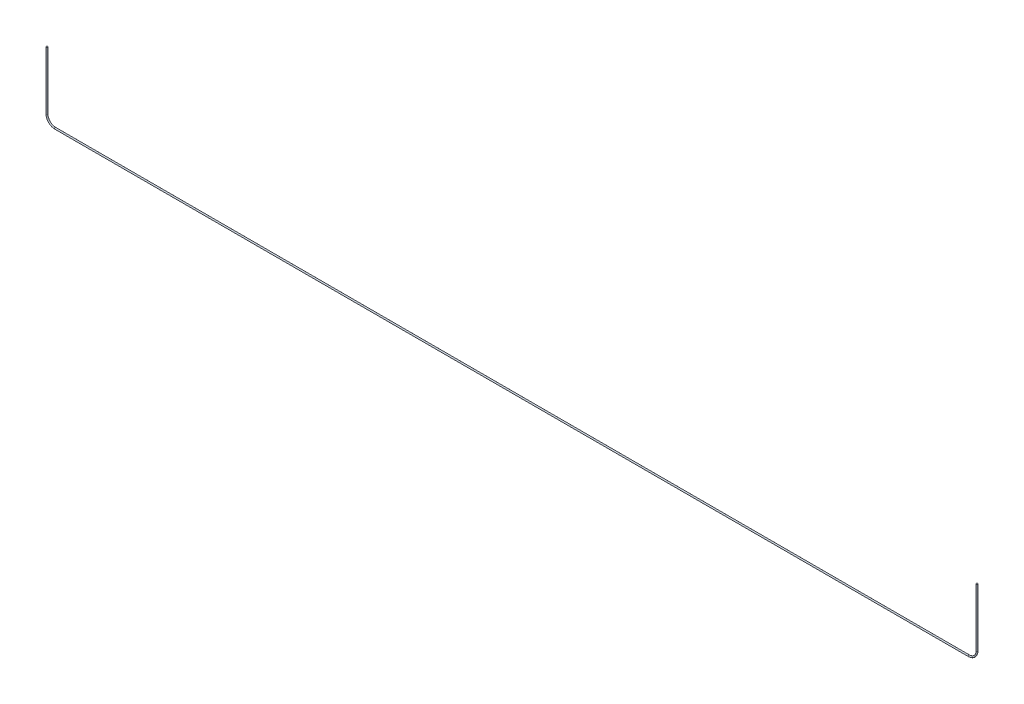
SolidWorks part; units mm, degrees
ref_plane "Front Plane" through (0, 0, 0) normal (0, 0, 1) x (1, 0, 0)
ref_plane "Top Plane" through (0, 0, 0) normal (0, 1, 0) x (1, 0, 0)
ref_plane "Right Plane" through (0, 0, 0) normal (1, 0, 0) x (0, 0, -1)
sketch "Sketch1" plane through (0, 0, 0) normal (0, 0, 1) x (1, 0, 0)
  line L0 (4125, 0) -> (-4125, 0)
  line L1 (-4200, 75) -> (-4200, 600)
  line L2 (0, 679.5766) -> (0, -698.3937) construction
  line L3 (4200, 75) -> (4200, 600)
  arc A0 (-4125, 0) -> (-4200, 75) centre (-4125, 75) cw
  arc A1 (4125, 0) -> (4200, 75) centre (4125, 75) ccw
  point P6 (-4200, 0)
  point P12 (0, 0)
  dimension "D3" = 75
  dimension "D1" = 4200
  dimension "D2" = 600
sweep "Sweep1" add path "Sketch1" circular profile diameter 12.7 parameters "D3"=12.7
